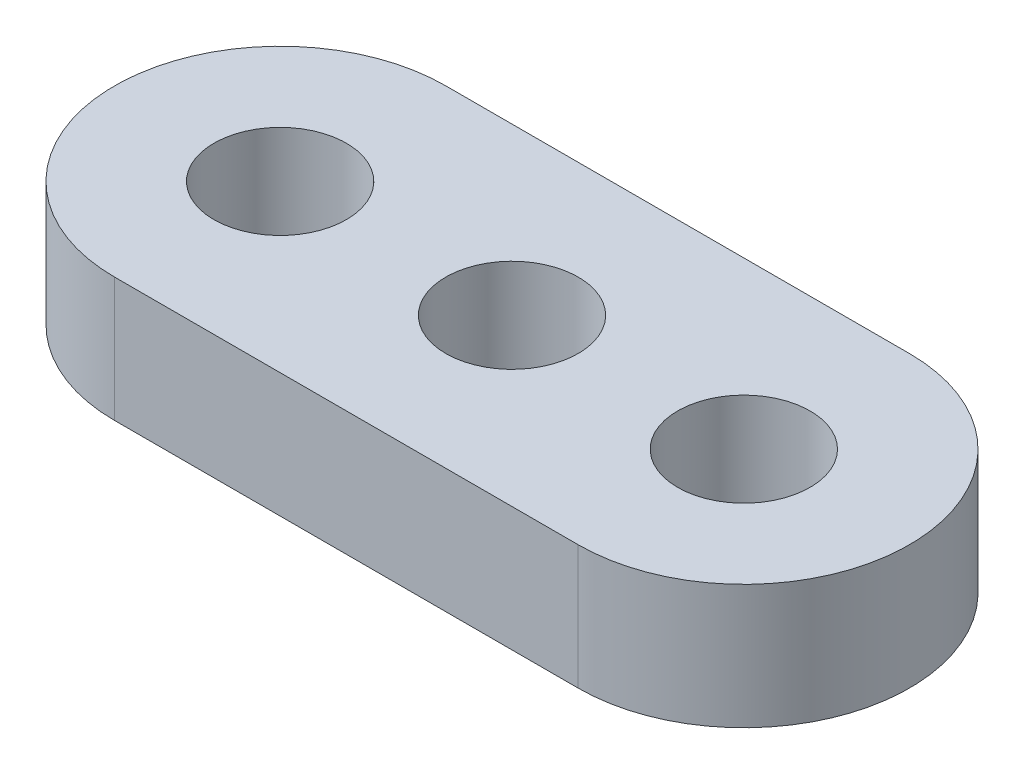
SolidWorks part; units mm, degrees
ref_plane "正面" through (0, 0, 0) normal (0, 0, 1) x (1, 0, 0)
ref_plane "平面" through (0, 0, 0) normal (0, 1, 0) x (1, 0, 0)
ref_plane "右側面" through (0, 0, 0) normal (1, 0, 0) x (0, 0, -1)
sketch "ｽｹｯﾁ1" plane through (0, 0, 0) normal (0, 1, 0) x (1, 0, 0)
  line L0 (-5.6, 0) -> (5.6, 0) construction
  line L1 (-5.6, 4) -> (5.6, 4)
  line L2 (-5.6, -4) -> (5.6, -4)
  arc A0 (-5.6, 4) -> (-5.6, -4) centre (-5.6, 0) ccw
  arc A1 (5.6, -4) -> (5.6, 4) centre (5.6, 0) ccw
  circle A2 centre (-5.6, 0) radius 1.6
  circle A3 centre (5.6, 0) radius 1.6
  circle A4 centre (0, 0) radius 1.6
  point P2 (0, 0)
  dimension "D2" = 3.2
  dimension "D3" = 4
  dimension "D4" = 3.2
  dimension "D1" = 11.2
extrude "ﾎﾞｽ - 押し出し1" add sketch "ｽｹｯﾁ1" along normal blind 3
